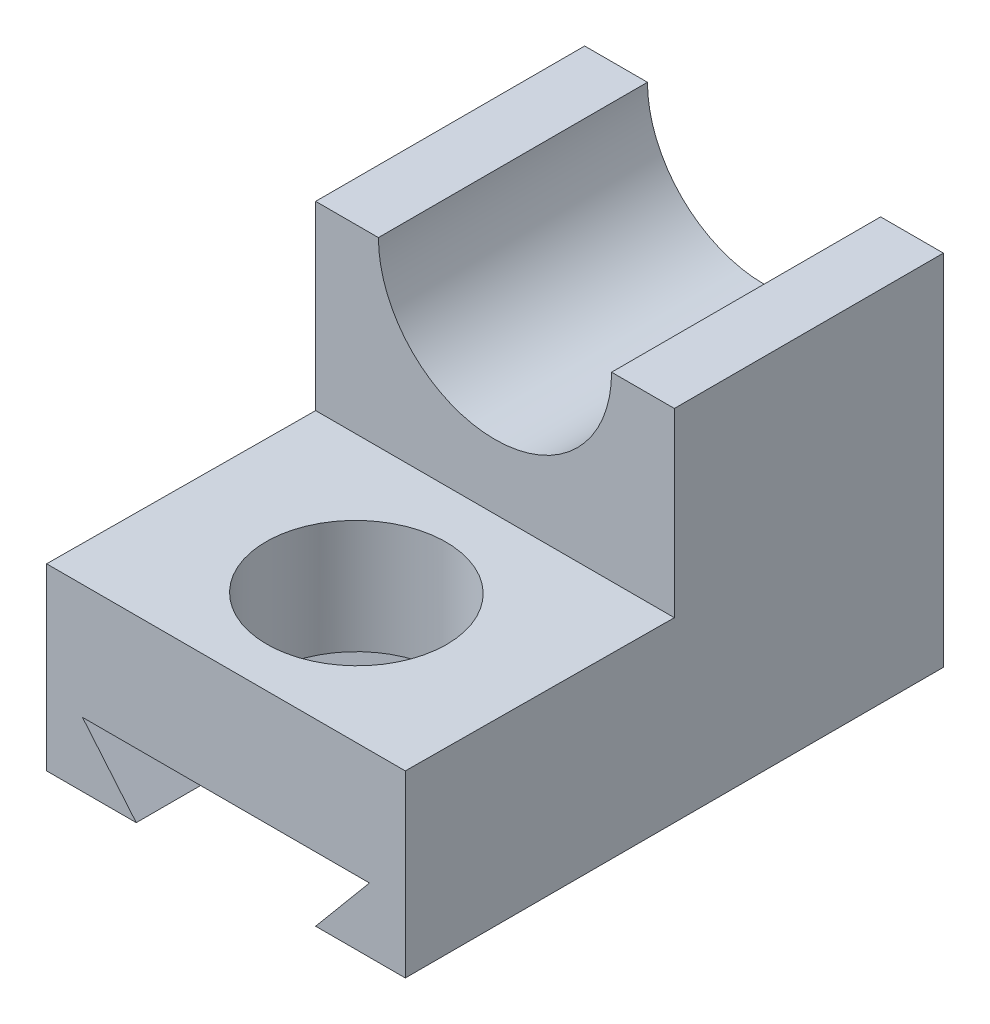
SolidWorks part; units mm, degrees
ref_plane "前视基准面" through (0, 0, 0) normal (0, 0, 1) x (1, 0, 0)
ref_plane "上视基准面" through (0, 0, 0) normal (0, 1, 0) x (1, 0, 0)
ref_plane "右视基准面" through (0, 0, 0) normal (1, 0, 0) x (0, 0, -1)
sketch "草图1" plane through (0, 0, 0) normal (0, 0, 1) x (1, 0, 0)
  line L0 (0, 54.1865) -> (0, -64.7386) construction
  line L2 (-57.6088, 0) -> (45.9159, 0) construction
sketch "草图2" plane through (0, 0, 0) normal (1, 0, 0) x (0, 0, -1)
  line L1 (0, 508) -> (762, 508)
  line L2 (-762, 0) -> (-762, -508)
  line L3 (-762, -508) -> (762, -508)
  line L4 (762, 508) -> (762, -508)
  line L8 (-762, 0) -> (0, -5.2761)
  line L9 (0, 200054.1865) -> (0, -200064.7386) construction
  line L10 (0, -5.2761) -> (0, 508)
extrude "凸台-拉伸1" add sketch "草图2" along normal mid plane 1016
sketch "草图3" plane through (0, 0, 0) normal (0, 0, 1) x (1, 0, 0)
  line L0 (508, 508) -> (-508, 508) construction
  line L6 (-330.2, 508) -> (330.2, 508)
  line L7 (508, 508) -> (508, -5.2761) construction
  arc A0 (-330.2, 508) -> (330.2, 508) centre (0, 508) ccw
  point P1 (0, 0)
extrude "切除-拉伸1" cut sketch "草图3" against normal through all both
sketch "草图4" plane through (0, 0, 0) normal (0, 0, 1) x (1, 0, 0)
  line L0 (-406.4, -325.7798) -> (406.4, -325.7798)
  line L2 (508, -508) -> (-508, -508) construction
  line L3 (254, -508) -> (-254, -508)
  line L10 (-254, -508) -> (-406.4, -325.7798)
  line L11 (254, -508) -> (406.4, -325.7798)
extrude "切除-拉伸2" cut sketch "草图4" along direction (0, 0, -1) on the side against the normal through all both and the other way through all
sketch "草图5" plane through (0, 0, 0) normal (0, 1, 0) x (1, 0, 0)
  line L0 (0, -1101.418) -> (0, 1101.418) construction
  circle A0 centre (0, -392.6917) radius 254
extrude "切除-拉伸3" cut sketch "草图5" against normal through all both
